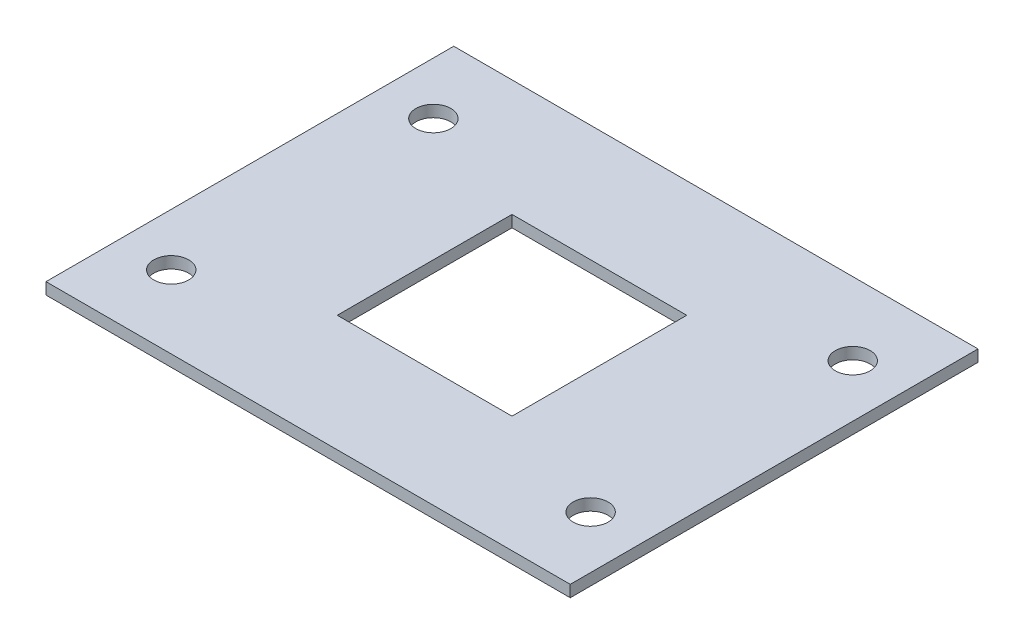
SolidWorks part; units mm, degrees
ref_plane "Alzado" through (0, 0, 0) normal (0, 0, 1) x (1, 0, 0)
ref_plane "Planta" through (0, 0, 0) normal (0, 1, 0) x (1, 0, 0)
ref_plane "Vista lateral" through (0, 0, 0) normal (1, 0, 0) x (0, 0, -1)
sketch "Croquis1" plane through (0, 0, 0) normal (0, 1, 0) x (1, 0, 0)
  line L0 (0, 0) -> (15, 15) construction
  line L1 (0, 0) -> (15, 0)
  line L2 (0, 0) -> (0, 15)
  line L3 (0, 15) -> (15, 15)
  line L4 (15, 0) -> (15, 15)
  line L5 (-15, -15) -> (30, -15)
  line L6 (-15, -15) -> (-15, 30)
  line L7 (-15, 30) -> (30, 30)
  line L8 (30, -15) -> (30, 30)
  line L9 (-15, 30) -> (30, -15) construction
  line L10 (-17.4749, 32.4749) -> (-15, 30) construction
  line L11 (25.5, 7.5) -> (30, 7.5) construction
  line L12 (7.5, 7.5) -> (7.5, -17.4738) construction
  line L13 (7.5, 7.5) -> (0, 7.5) construction
  line L14 (7.5, 22.5) -> (7.5, 30) construction
  line L15 (-7.5, 22.5) -> (22.5, 22.5) construction
  line L16 (-7.5, 22.5) -> (-7.5, -7.5) construction
  line L17 (-7.5, -7.5) -> (22.5, -7.5) construction
  line L18 (22.5, 22.5) -> (22.5, -7.5) construction
  line L19 (-7.5, 22.5) -> (22.5, -7.5) construction
  line L20 (-7.5, -7.5) -> (22.5, 22.5) construction
  line L21 (25.5, -3.75) -> (25.5, 7.5) construction
  line L22 (25.5, 7.5) -> (25.5, 18.75) construction
  line L23 (0.5, 25) -> (7.5, 25) construction
  line L24 (7.5, 25) -> (14.5, 25) construction
  circle A4 centre (-10.5, 18.75) radius 1.5
  circle A5 centre (-10.5, -3.75) radius 1.5
  arc A12 (-15, -14.8985) -> (-14.8985, -15) centre (-12.4749, -12.4749) ccw
  circle A23 centre (25.5, 18.75) radius 1.5
  circle A24 centre (25.5, -3.75) radius 1.5
  point P9 (7.5, 7.5)
  point P10 (7.5, 7.5)
  dimension "D3" = 18
  dimension "D9" = 3
  dimension "D1" = 15
  dimension "D2" = 45
  dimension "D5" = 3.5
  dimension "D6" = 7
  dimension "D8" = 30
  dimension "D10" = 11.25
  dimension "D7" = 17.5
extrude "Saliente-Extruir1" add sketch "Croquis1" along normal blind 1
sketch "Croquis2" plane through (0, 1, 0) normal (0, 1, 0) x (1, 0, 0)
  line L0 (-15, -14.8985) -> (-15, 30) construction
  line L1 (30, -15) -> (-15, -15)
  line L2 (30, -15) -> (30, -10)
  line L3 (30, -10) -> (-15, -10)
  line L4 (-15, -15) -> (-15, -10)
  line L6 (30, 30) -> (-15, 30)
  line L7 (30, 30) -> (30, 25)
  line L8 (30, 25) -> (-15, 25)
  line L9 (-15, 30) -> (-15, 25)
  dimension "D1" = 5
extrude "Cortar-Extruir1" cut sketch "Croquis2" against normal blind 10
